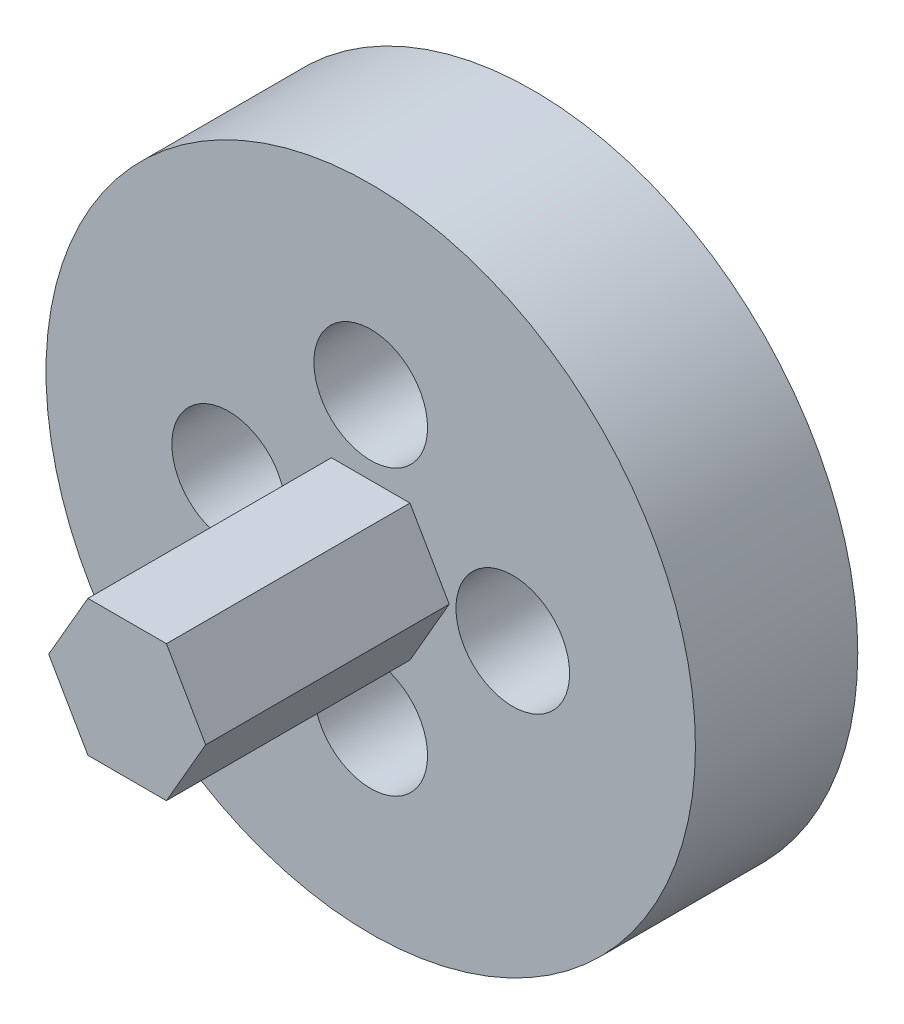
SolidWorks part; units mm, degrees
ref_plane "Front Plane" through (0, 0, 0) normal (0, 0, 1) x (1, 0, 0)
ref_plane "Top Plane" through (0, 0, 0) normal (0, 1, 0) x (1, 0, 0)
ref_plane "Right Plane" through (0, 0, 0) normal (1, 0, 0) x (0, 0, -1)
sketch "Sketch1" plane through (0, 0, 0) normal (0, 0, 1) x (1, 0, 0)
  circle A0 centre (0, 0) radius 10
  circle A1 centre (0, 7) radius 1.65
  circle A2 centre (7, 0) radius 1.65
  circle A3 centre (0, -7) radius 1.65
  circle A4 centre (-7, 0) radius 1.65
  point P5 (8.1889, -2.9172)
  point P6 (0, 0)
  point P14 (0, 0)
  dimension "D1" = 20
  dimension "D2" = 3.3
  dimension "D3" = 7
  dimension "D4" = 4
extrude "Boss-Extrude1" add sketch "Sketch1" along normal blind 2
sketch "Sketch2" plane through (0, 0, 2) normal (0, 0, 1) x (1, 0, 0)
  circle A0 centre (0, 0) radius 16
  dimension "D1" = 32
extrude "Boss-Extrude2" add sketch "Sketch2" along normal blind 8
sketch "Sketch3" plane through (0, 0, 10) normal (0, 0, 1) x (1, 0, 0)
  line L1 (3.8682, 0) -> (1.9341, 3.35)
  line L2 (1.9341, 3.35) -> (-1.9341, 3.35)
  line L3 (-1.9341, 3.35) -> (-3.8682, 0)
  line L4 (-3.8682, 0) -> (-1.9341, -3.35)
  line L5 (-1.9341, -3.35) -> (1.9341, -3.35)
  line L6 (1.9341, -3.35) -> (3.8682, 0)
  circle A0 centre (0, 0) radius 3.35 construction
  dimension "D1" = 6.7
extrude "Boss-Extrude3" add sketch "Sketch3" along normal blind 12
sketch "Sketch4" plane through (0, 0, 0) normal (0, 0, -1) x (-1, 0, 0)
  circle A0 centre (0, -7) radius 1.65 construction
  circle A1 centre (-7, 0) radius 1.65 construction
  circle A2 centre (7, 0) radius 1.65 construction
  circle A3 centre (0, 7) radius 1.65 construction
  circle A4 centre (0, -7) radius 1.65
  circle A5 centre (-7, 0) radius 1.65
  circle A6 centre (7, 0) radius 1.65
  circle A7 centre (0, 7) radius 1.65
extrude "Cut-Extrude1" cut sketch "Sketch4" against normal blind 12
sketch "Sketch5" plane through (0, 0, 10) normal (0, 0, 1) x (1, 0, 0)
  circle A0 centre (0, 7) radius 2.8
  circle A2 centre (7, 0) radius 2.8
  circle A3 centre (0, -7) radius 2.8
  circle A4 centre (-7, 0) radius 2.8
  point P3 (9.08, -2.6099)
  point P4 (0, 0)
  point P13 (0, 0)
  dimension "D1" = 5.6
  dimension "D2" = 4
extrude "Cut-Extrude2" cut sketch "Sketch5" against normal blind 5.6
